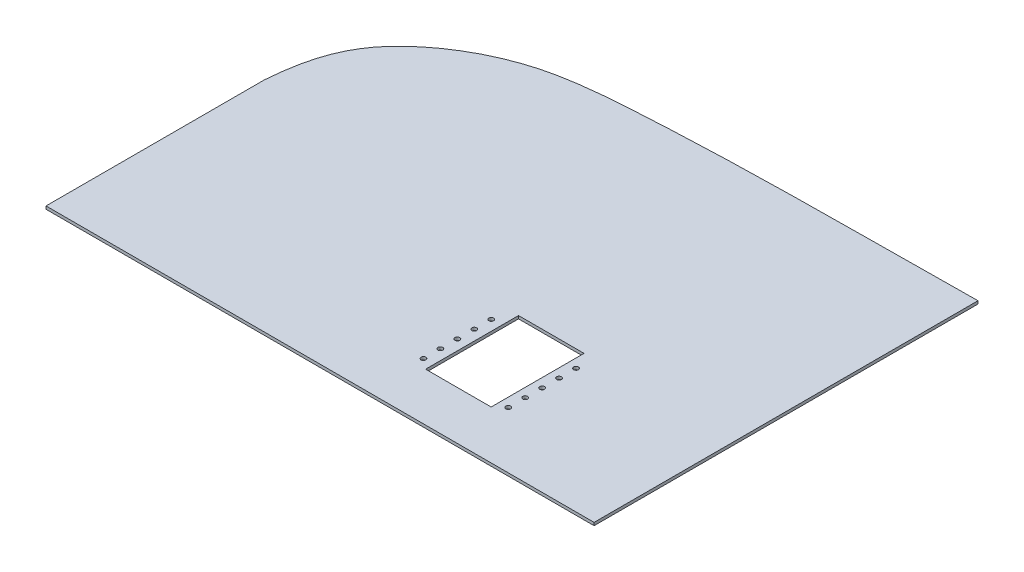
SolidWorks part; units mm, degrees
ref_plane "Alzado" through (0, 0, 0) normal (0, 0, 1) x (1, 0, 0)
ref_plane "Planta" through (0, 0, 0) normal (0, 1, 0) x (1, 0, 0)
ref_plane "Vista lateral" through (0, 0, 0) normal (1, 0, 0) x (0, 0, -1)
sketch "Croquis1" plane through (0, 0, 0) normal (0, 1, 0) x (1, 0, 0)
  line L0 (-226.279, 0) -> (226.279, 0)
  line L1 (226.279, 0) -> (226.279, 317)
  line L3 (47.179, 40) -> (101.279, 40)
  line L4 (47.179, 40) -> (47.179, 116.7)
  line L5 (47.179, 116.7) -> (101.279, 116.7)
  line L6 (101.279, 40) -> (101.279, 116.7)
  line L16 (-226.279, 0) -> (-226.279, 180)
  circle A0 centre (38.679, 102.7) radius 2
  circle A1 centre (108.679, 102.7) radius 2
  circle A2 centre (108.679, 88.7) radius 2
  circle A3 centre (108.679, 74.7) radius 2
  circle A4 centre (108.679, 60.7) radius 2
  circle A5 centre (108.679, 46.7) radius 2
  circle A6 centre (38.679, 88.7) radius 2
  circle A7 centre (38.679, 74.7) radius 2
  circle A8 centre (38.679, 60.7) radius 2
  circle A9 centre (38.679, 46.7) radius 2
  spline S0 degree 3 poles (-226.279, 180) (-223.6672, 215.4766) (-213.4119, 241.7289) (-180.591, 273.8979) (-156.3503, 289.27) (-113.0678, 305.0472) (-89.4215, 307.6374) (-74, 309.1757) knots 0 0 0 0 0.358065 0.430061 0.687747 0.747962 1 1 1 1
  spline S1 degree 3 poles (226.279, 317) (126.0586, 315.5305) (25.9571, 316.9126) (-74, 309.1757) knots 0 0 0 0 1 1 1 1
  point P4 (0, 0)
  point P11 (226.279, 318)
  point P12 (226.279, 318)
  point P13 (226.279, 318)
  point P33 (226.279, 318)
  dimension "D7" = 4
  dimension "D8" = 8.5
  dimension "D12" = 317
  dimension "D2" = 180
  dimension "D3" = 76.7
  dimension "D4" = 54.1
  dimension "D5" = 125
  dimension "D6" = 40
  dimension "D9" = 14
  dimension "D10" = 2
  dimension "D11" = 5
extrude "Saliente-Extruir1" add sketch "Croquis1" along normal blind 2.4
